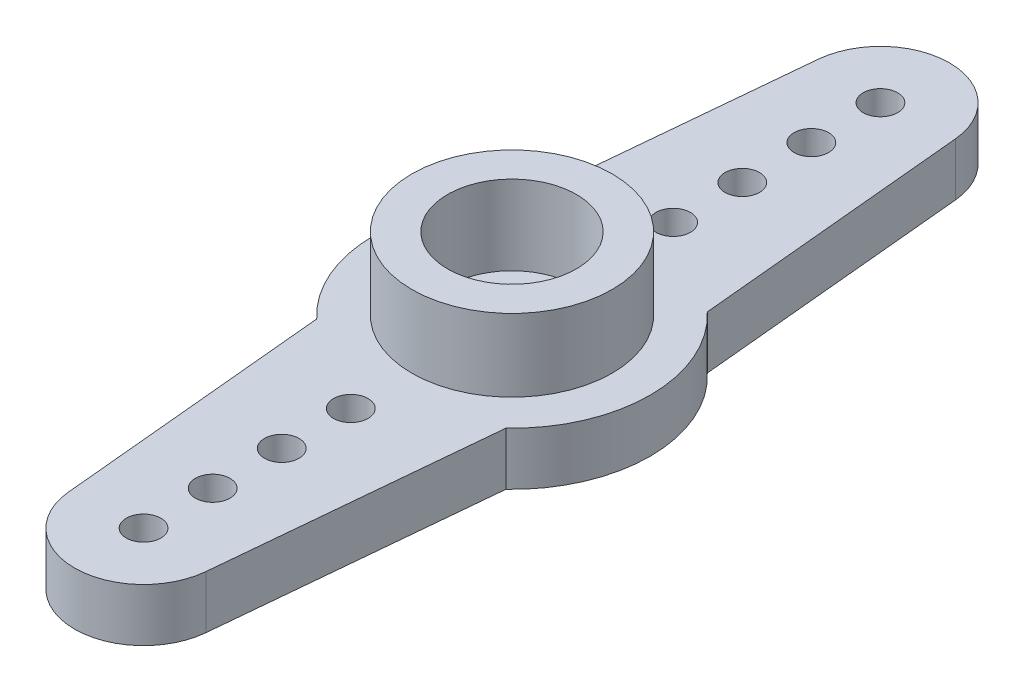
SolidWorks part; units mm, degrees
ref_plane "Front Plane" through (0, 0, 0) normal (0, 0, 1) x (1, 0, 0)
ref_plane "Top Plane" through (0, 0, 0) normal (0, 1, 0) x (1, 0, 0)
ref_plane "Right Plane" through (0, 0, 0) normal (1, 0, 0) x (0, 0, -1)
sketch "Sketch1" plane through (0, 0, 0) normal (0, 1, 0) x (1, 0, 0)
  circle A0 centre (0, 0) radius 4.35
  circle A1 centre (0, 0) radius 2.8
  dimension "D1" = 5.6
  dimension "D2" = 8.7
extrude "Boss-Extrude1" add sketch "Sketch1" along normal blind 5.45
sketch "Sketch2" plane through (0, 0, 0) normal (0, 1, 0) x (1, 0, 0)
  line L0 (-2.9868, 16.2812) -> (-4.1081, 4.373)
  line L1 (-4.1081, -4.373) -> (-2.9868, -16.2812)
  line L2 (4.4802, -0.4219) -> (4.5199, 0)
  line L3 (2.9868, -16.2812) -> (4.1081, -4.373)
  line L4 (4.5199, 0) -> (4.4802, 0.4219)
  line L5 (4.1081, 4.373) -> (2.9868, 16.2812)
  arc A0 (-4.1081, 4.373) -> (-4.1081, -4.373) centre (0, 0) ccw
  arc A1 (2.9868, 16.2812) -> (-2.9868, 16.2812) centre (0, 16) ccw
  arc A2 (-2.9868, -16.2812) -> (2.9868, -16.2812) centre (0, -16) ccw
  arc A3 (4.4802, -0.4219) -> (4.4802, 0.4219) centre (0, 0) ccw construction
  arc A4 (4.1081, -4.373) -> (4.1081, 4.373) centre (0, 0) ccw
  circle A5 centre (0, 0) radius 2.8 construction
  circle A6 centre (0, 0) radius 2.8
  point P6 (5.3975, 8.042)
  point P8 (5.8133, 1.0078)
  point P9 (-5.9, -3.2367)
  point P11 (6.4871, -5.6658)
  dimension "D1" = 12
  dimension "D2" = 6
  dimension "D3" = 6
  dimension "D6" = 9
  dimension "D4" = 32
  dimension "D5" = 16
extrude "Boss-Extrude2" add sketch "Sketch2" along normal blind 2.3
sketch "Sketch3" plane through (0, 0, 0) normal (0, 1, 0) x (1, 0, 0)
  circle A0 centre (0, 7) radius 0.75
  point P2 (0, 7.629)
  point P4 (0.8191, 6.9519)
  dimension "D2" = 1.5
  dimension "D1" = 7
extrude "Cut-Extrude2" cut sketch "Sketch3" along normal up to next
pattern_linear "LPattern1" count 4 spacing 3 along (0, 0, -1) of "Cut-Extrude2"
mirror "Mirror1" about plane through (0, 0, 0) normal (0, 0, 1) of "LPattern1", "Cut-Extrude2"
sketch "Sketch5" plane through (0, 0, 0) normal (0, 1, 0) x (1, 0, 0)
  circle A0 centre (0, 0) radius 1.5
  circle A1 centre (0, 0) radius 2.8 construction
  circle A2 centre (0, 0) radius 2.8
  dimension "D1" = 3
extrude "Boss-Extrude3" add sketch "Sketch5" along normal blind 2
